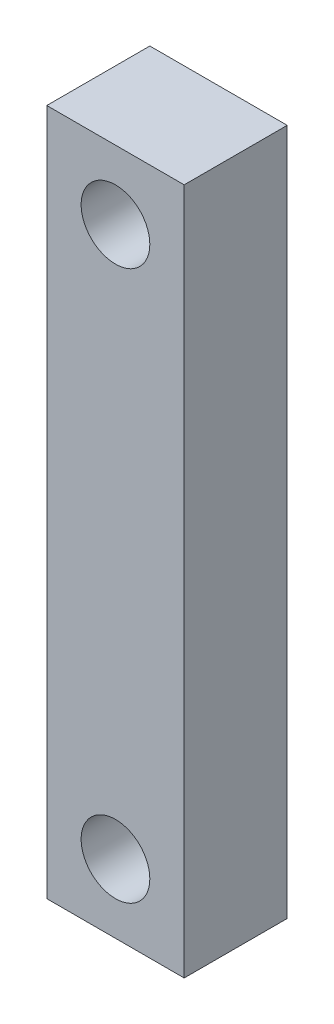
SolidWorks part; units mm, degrees
ref_plane "Front Plane" through (0, 0, 0) normal (0, 0, 1) x (1, 0, 0)
ref_plane "Top Plane" through (0, 0, 0) normal (0, 1, 0) x (1, 0, 0)
ref_plane "Right Plane" through (0, 0, 0) normal (1, 0, 0) x (0, 0, -1)
sketch "Sketch1" plane through (0, 0, 0) normal (0, 0, 1) x (1, 0, 0)
  line L1 (-10, 50) -> (10, 50)
  line L2 (-10, 50) -> (-10, -50)
  line L3 (-10, -50) -> (10, -50)
  line L4 (10, 50) -> (10, -50)
  line L5 (-10, 50) -> (10, -50) construction
  line L6 (-10, -50) -> (10, 50) construction
  point P0 (0, 0)
  dimension "D1" = 20
  dimension "D2" = 100
extrude "Boss-Extrude1" add sketch "Sketch1" along normal blind 15
sketch "Sketch2" plane through (0, 0, 15) normal (0, 0, 1) x (1, 0, 0)
  line L0 (10, 50) -> (-10, 50) construction
  circle A0 centre (0, 40) radius 5
  circle A1 centre (0, -40) radius 5
  dimension "D1" = 80
  dimension "D2" = 10
extrude "Cut-Extrude1" cut sketch "Sketch2" against normal blind 15
